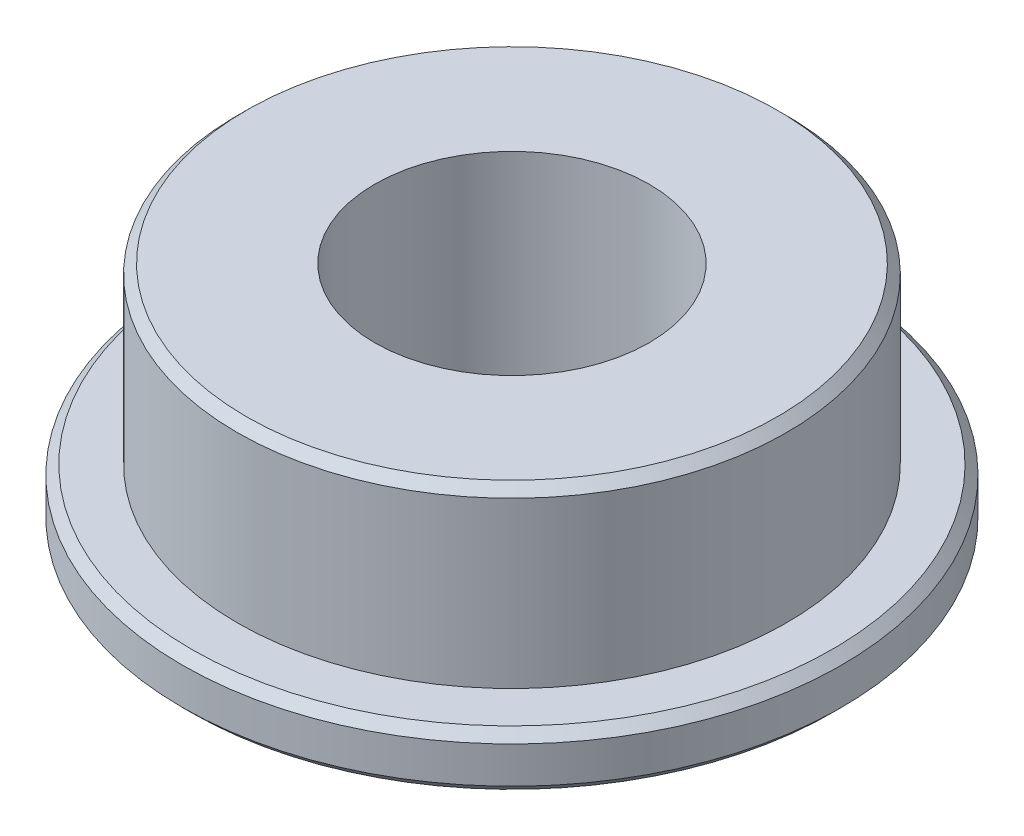
SolidWorks part; units mm, degrees
ref_plane "前视基准面" through (0, 0, 0) normal (0, 0, 1) x (1, 0, 0)
ref_plane "上视基准面" through (0, 0, 0) normal (0, 1, 0) x (1, 0, 0)
ref_plane "右视基准面" through (0, 0, 0) normal (1, 0, 0) x (0, 0, -1)
other "Configuration Table"
sketch "草图1" plane through (0, 0, 0) normal (0, 1, 0) x (1, 0, 0)
  circle A0 centre (0, 0) radius 1.5
  circle A1 centre (0, 0) radius 3.6
  dimension "D1" = 3
  dimension "D2" = 7.2
extrude "凸台-拉伸1" add sketch "草图1" along normal blind 2.5
sketch "草图2" plane through (0, 2.5, 0) normal (0, 1, 0) x (1, 0, 0)
  circle A0 centre (0, 0) radius 3
  circle A1 centre (0, 0) radius 3.6
  dimension "D1" = 7.2
  dimension "D2" = 6
extrude "切除-拉伸1" cut sketch "草图2" against normal blind 1.9
chamfer "倒角1" distance 0.1 angle 45 3 edges at (0, 0, 3.6) (0, 0.6, 3.6) (0, 2.5, 3)
